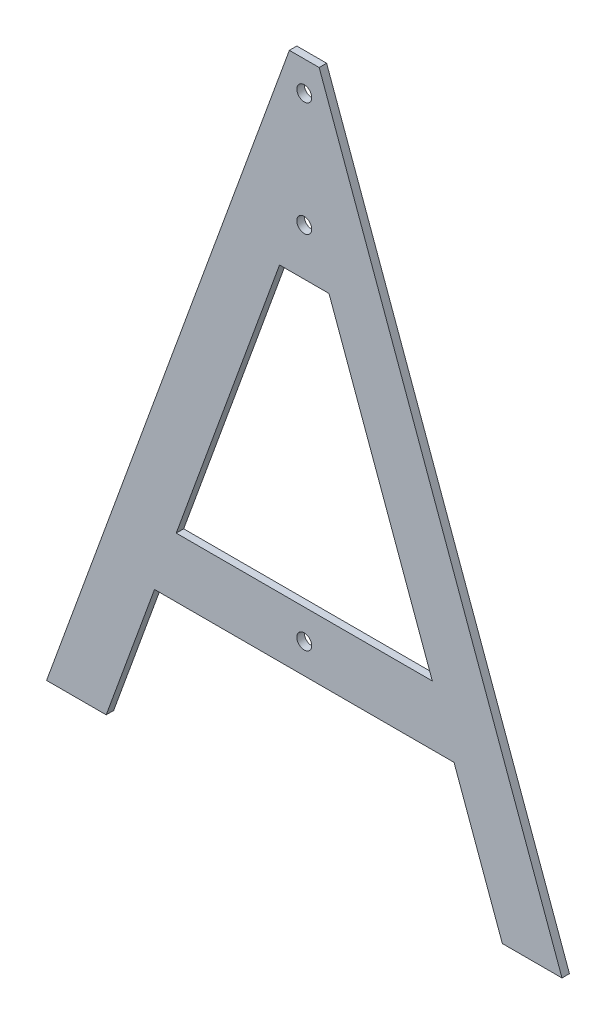
SolidWorks part; units mm, degrees
ref_plane "Front Plane" through (0, 0, 0) normal (0, 0, 1) x (1, 0, 0)
ref_plane "Top Plane" through (0, 0, 0) normal (0, 1, 0) x (1, 0, 0)
ref_plane "Right Plane" through (0, 0, 0) normal (1, 0, 0) x (0, 0, -1)
sketch "Sketch1" plane through (0, 0, 0) normal (0, 0, 1) x (1, 0, 0)
  line L0 (0, 0) -> (0, -48.5585) construction
  line L1 (0, 0) -> (0, 12.7) construction
  line L2 (6.35, 12.7) -> (-6.35, 12.7)
  line L3 (0, -48.5585) -> (0, -271.4435) construction
  line L4 (6.35, 12.7) -> (109.7698, -271.4434)
  line L5 (109.7698, -271.4434) -> (84.3698, -271.4435)
  line L6 (54.5411, -189.4899) -> (10.5276, -68.5638)
  line L7 (-54.5411, -189.4899) -> (-10.5276, -68.5638)
  line L8 (-109.7698, -271.4434) -> (-84.3698, -271.4435)
  line L9 (-6.35, 12.7) -> (-109.7698, -271.4434)
  line L10 (-10.5276, -68.5638) -> (10.5276, -68.5638)
  line L11 (-54.5411, -189.4899) -> (54.5411, -189.4899)
  line L12 (-54.5411, -189.4899) -> (-54.5411, -214.8899) construction
  line L13 (-63.786, -214.8899) -> (63.786, -214.8899)
  line L14 (84.3698, -271.4435) -> (63.786, -214.8899)
  line L15 (-84.3698, -271.4435) -> (-63.786, -214.8899)
  circle A0 centre (0, 0) radius 3.175
  circle A1 centre (0, -48.5585) radius 3.175
  circle A2 centre (0, -214.8899) radius 12.7 construction
  circle A3 centre (0, -202.1899) radius 3.175
  point P10 (0, 12.7)
  dimension "D1" = 6.35
  dimension "D3" = 6.35
  dimension "D12" = 25.4
  dimension "D13" = 6.35
  dimension "D2" = 48.5585
  dimension "D4" = 12.7
  dimension "D5" = 12.7
  dimension "D6" = 222.885
  dimension "D7" = 284.1435
  dimension "D8" = 25.4
  dimension "D9" = 215.9
  dimension "D10" = 250
  dimension "D11" = 25.4
extrude "Boss-Extrude1" add sketch "Sketch1" along normal blind 3.175
